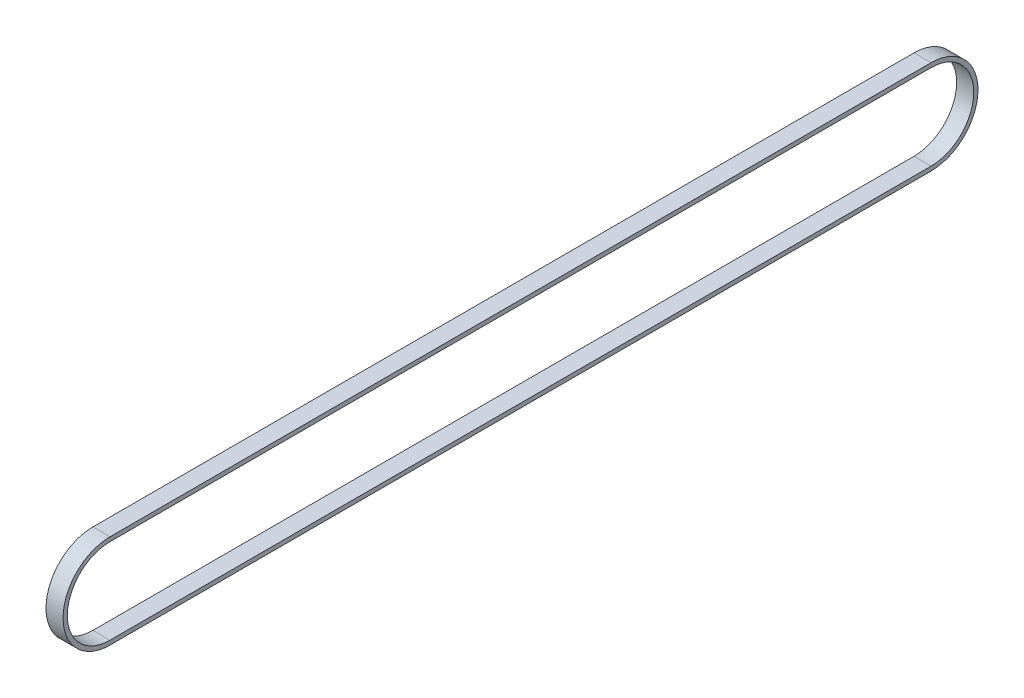
SolidWorks part; units mm, degrees
ref_plane "前视基准面" through (0, 0, 0) normal (0, 0, 1) x (1, 0, 0)
ref_plane "上视基准面" through (0, 0, 0) normal (0, 1, 0) x (1, 0, 0)
ref_plane "右视基准面" through (0, 0, 0) normal (1, 0, 0) x (0, 0, -1)
sketch "草图1" plane through (0, 0, 0) normal (1, 0, 0) x (0, 0, -1)
  line L0 (-192.5, 0) -> (192.5, 0) construction
  line L1 (-192.5, 20) -> (192.5, 20)
  line L2 (-192.5, -20) -> (192.5, -20)
  arc A0 (-192.5, 20) -> (-192.5, -20) centre (-192.5, 0) ccw
  arc A1 (192.5, -20) -> (192.5, 20) centre (192.5, 0) ccw
  point P3 (0, 0)
  point P8 (0, 0)
  dimension "D2" = 20
  dimension "D1" = 385
extrude "拉伸-薄壁1" add sketch "草图1" along normal mid plane 8 thin thin type one direction wall 2
